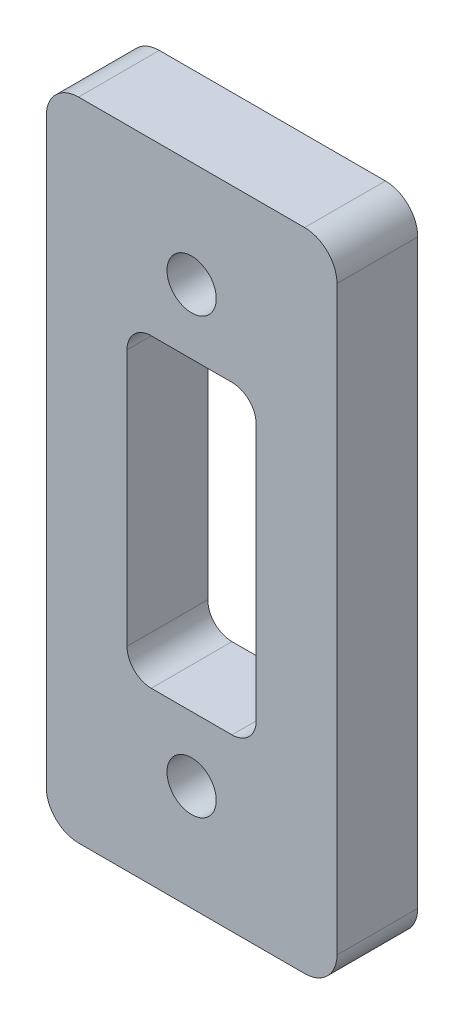
SolidWorks part; units mm, degrees
material "A-玻璃纤维"
ref_plane "前视基准面" through (0, 0, 0) normal (0, 0, 1) x (1, 0, 0)
ref_plane "上视基准面" through (0, 0, 0) normal (0, 1, 0) x (1, 0, 0)
ref_plane "右视基准面" through (0, 0, 0) normal (1, 0, 0) x (0, 0, -1)
other "Configuration Table"
sketch "草图1" plane through (0, 0, 0) normal (0, 0, 1) x (1, 0, 0)
  line L0 (0, 0) -> (0, 13.45) construction
  line L1 (-9, -20) -> (9, -20)
  line L2 (-9, -20) -> (-9, 20)
  line L3 (-9, 20) -> (9, 20)
  line L4 (9, -20) -> (9, 20)
  line L5 (-9, -20) -> (9, 20) construction
  line L6 (-9, 20) -> (9, -20) construction
  line L7 (0, 0) -> (0, -13.45) construction
  circle A0 centre (0, 13.45) radius 1.525
  circle A1 centre (0, -13.45) radius 1.525
  point P0 (0, 0)
  dimension "D4" = 3.05
  dimension "D1" = 40
  dimension "D2" = 18
  dimension "D3" = 26.9
extrude "凸台-拉伸1" add sketch "草图1" along normal blind 5
fillet "圆角1" radius 2 4 edges at (9, -20, 2.5) (-9, -20, 2.5) (-9, 20, 2.5) (9, 20, 2.5)
sketch "草图2" plane through (0, 0, 5) normal (0, 0, 1) x (1, 0, 0)
  line L0 (9, -18) -> (9, 18) construction
  line L1 (-4, -9.45) -> (4, -9.45)
  line L2 (-4, -9.45) -> (-4, 9.45)
  line L3 (-4, 9.45) -> (4, 9.45)
  line L4 (4, -9.45) -> (4, 9.45)
  line L5 (-4, -9.45) -> (4, 9.45) construction
  line L6 (-4, 9.45) -> (4, -9.45) construction
  circle A0 centre (0, 13.45) radius 1.525 construction
  point P0 (0, 0)
  dimension "D1" = 5
  dimension "D2" = 4
extrude "切除-拉伸1" cut sketch "草图2" against normal blind 5
fillet "圆角2" radius 1.5 4 edges at (-4, 9.45, 2.5) (4, 9.45, 2.5) (4, -9.45, 2.5) (-4, -9.45, 2.5)
